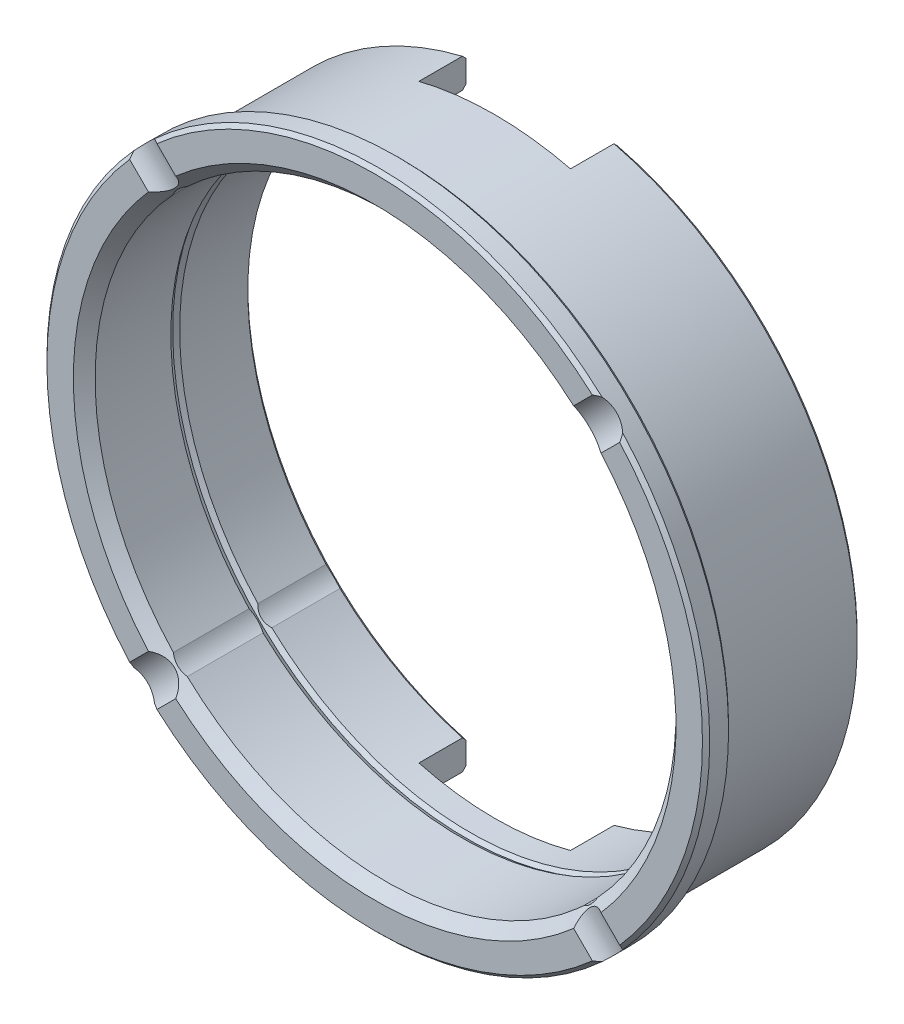
SolidWorks part; units mm, degrees
material "PB01 (C90710) Bronze"
ref_plane "Front" through (0, 0, 0) normal (0, 0, 1) x (1, 0, 0)
ref_plane "Top" through (0, 0, 0) normal (0, 1, 0) x (1, 0, 0)
ref_plane "Right" through (0, 0, 0) normal (1, 0, 0) x (0, 0, -1)
other "Graphic2"
other "Graphic1"
sketch "Sketch32 (Mesh)_152" plane through (0, 0, 0) normal (1, 0, 0) x (0, 0, -1)
  line L1 (0, 0) -> (-24.65, 0) construction
  line L2 (-5.5, -40.4) -> (-5.5, -39.0018) construction
  line L3 (-16.55, -40.05) -> (-6.1062, -40.05)
  line L4 (-14.45, -44) -> (4.5, -44)
  line L5 (-18.05, -45.2) -> (-18.05, -41.55)
  line L6 (-5.5, -40.4) -> (-6.1062, -40.05)
  line L7 (-17.55, -45.7) -> (-14.95, -45.7)
  line L8 (-4.8938, -40.05) -> (4.5, -40.05)
  line L9 (-18.05, -41.55) -> (-16.55, -40.05)
  line L10 (-14.45, -45.2) -> (-14.45, -44)
  line L11 (5, -43.5) -> (5, -40.55)
  line L12 (-4.8938, -40.05) -> (-5.5, -40.4)
  line L13 (-17.55, -45.7) -> (-18.05, -45.2)
  line L14 (-14.95, -45.7) -> (-14.45, -45.2)
  line L15 (4.5, -44) -> (5, -43.5)
  line L16 (4.5, -40.05) -> (5, -40.55)
  point P6 (-18.05, -40.05)
  point P9 (5, -44)
  point P10 (-18.05, -45.7)
  point P11 (-14.45, -45.7)
  point P13 (5, -40.05)
  dimension "D1" = 23.05
  dimension "D2" = 10.5
  dimension "D3" = 0.35
  dimension "D4" = 120
  dimension "D5" = 3.6
  dimension "D6" = 40.05
  dimension "D7" = 44
  dimension "D8" = 5
  dimension "D9" = 45.7
  dimension "D10" = 1.5
  dimension "D11" = 45
revolve "Revolve1" add sketch "Sketch32 (Mesh)_152" angle 360 about L1
sketch "Sketch33 (Mesh)_154" plane through (0, 0, 18.05) normal (0, 0, 1) x (1, 0, 0)
  line L0 (-50, 0) -> (50, 0) construction
  line L1 (-25.4558, 25.4558) -> (0, 0) construction
  line L2 (0, 0) -> (0, 27.1) construction
  circle A0 centre (0, 0) radius 36 construction
  circle A1 centre (-25.4558, 25.4558) radius 4.25
  point P12 (0, 0)
  dimension "D1" = 72
  dimension "D3" = 8.5
  dimension "D2" = 45
extrude "Cut-Extrude1" cut sketch "Sketch33 (Mesh)_154" against normal through all
ref_plane "Plane1" through (-28.3196, 28.3196, 0) normal (0.7071, -0.7071, 0) x (0, 0, -1)
sketch "Sketch34 (Mesh)_158" plane through (-28.3196, 28.3196, 0) normal (0.7071, -0.7071, 0) x (-0.7071, -0.7071, 0)
  circle A0 centre (0, -20.9) radius 3.9
  dimension "D1" = 7.8
  dimension "D2" = 20.9
extrude "Extrude21 (Cut)_159" cut sketch "Sketch34 (Mesh)_158" along normal mid plane 45
pattern_circular "CirPattern1" count 4 over 360 about axis through (0, 0, 0) along (0, 0, 1) of "Extrude21 (Cut)_159", "Cut-Extrude1"
sketch "Sketch35 (Mesh)_161" plane through (0, 0, 0) normal (0, 1, 0) x (1, 0, 0)
  line L0 (-50, 0) -> (74.5265, 0) construction
  line L1 (10.45, 5) -> (10.45, -1.5)
  line L2 (10.45, -1.5) -> (-10.45, -1.5)
  line L3 (0, 0.0243) -> (0, 12.55) construction
  line L4 (-10.45, -1.5) -> (-10.45, 5)
  line L5 (-10.45, 5) -> (10.45, 5)
  line L6 (40.55, 5) -> (-40.55, 5) construction
  dimension "D1" = 6.5
  dimension "D2" = 20.9
extrude "Cut-Extrude11" cut sketch "Sketch35 (Mesh)_161" along normal up to surface and the other way up to surface up to face at (0, 44, -4.5) other way up to face at (0, 44, -4.5)
